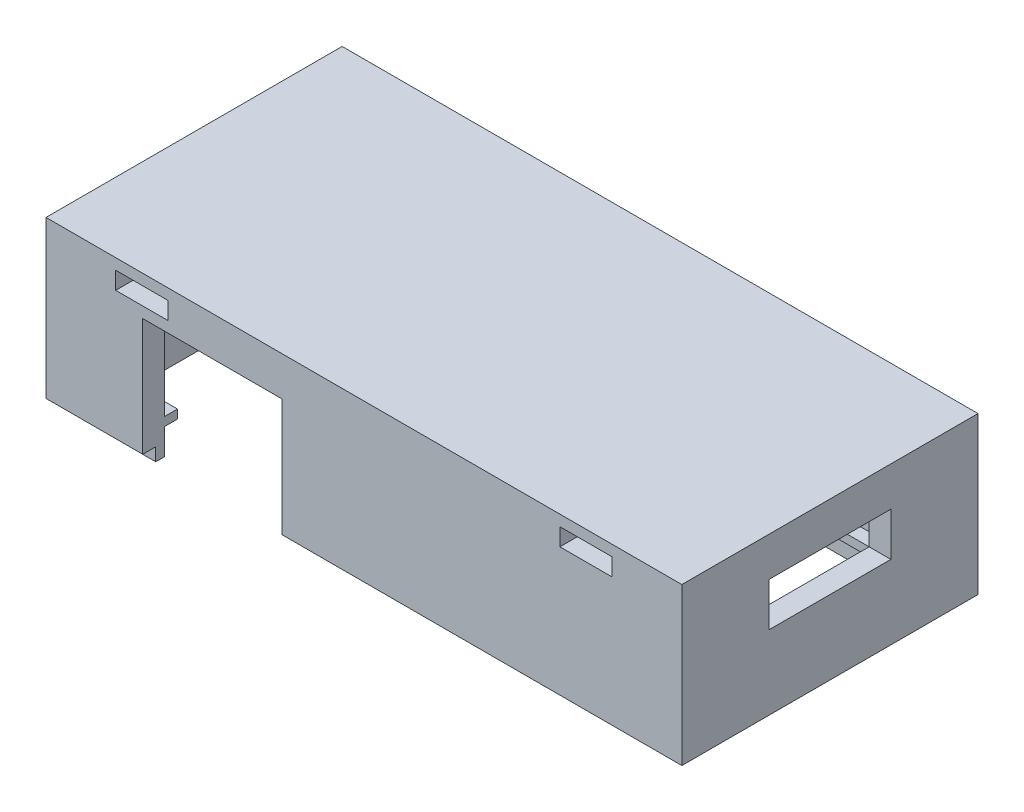
SolidWorks part; units mm, degrees
ref_plane "Front Plane" through (0, 0, 0) normal (0, 0, 1) x (1, 0, 0)
ref_plane "Top Plane" through (0, 0, 0) normal (0, 1, 0) x (1, 0, 0)
ref_plane "Right Plane" through (0, 0, 0) normal (1, 0, 0) x (0, 0, -1)
sketch "Sketch1" plane through (0, 0, 0) normal (0, 1, 0) x (1, 0, 0)
  line L1 (-31.2084, 17.8232) -> (41.7916, 17.8232)
  line L2 (-31.2084, 17.8232) -> (-31.2084, -16.1768)
  line L3 (-31.2084, -16.1768) -> (41.7916, -16.1768)
  line L4 (41.7916, 17.8232) -> (41.7916, -16.1768)
  dimension "D1" = 73
  dimension "D2" = 34
extrude "base" add sketch "Sketch1" along normal blind 4.5
sketch "Sketch21" plane through (0, 0, 0) normal (0, -1, 0) x (-1, 0, 0)
  line L11 (-41.7916, 17.8232) -> (31.2084, 17.8232)
  line L12 (-41.7916, 17.8232) -> (-41.7916, -16.1768)
  line L13 (-41.7916, -16.1768) -> (31.2084, -16.1768)
  line L14 (31.2084, 17.8232) -> (31.2084, -16.1768)
extrude "extrude up" add sketch "Sketch21" along normal blind 13.5
sketch "Sketch22" plane through (0, -13.5, 0) normal (0, -1, 0) x (-1, 0, 0)
  line L0 (-41.7916, 17.8232) -> (-41.7916, -16.1768) construction
  line L1 (-39.2916, 15.3232) -> (28.7084, 15.3232)
  line L2 (-39.2916, 15.3232) -> (-39.2916, -13.6768)
  line L3 (-39.2916, -13.6768) -> (28.7084, -13.6768)
  line L4 (28.7084, 15.3232) -> (28.7084, -13.6768)
  line L5 (31.2084, 17.8232) -> (-41.7916, 17.8232) construction
  line L6 (31.2084, -16.1768) -> (31.2084, 17.8232) construction
  line L7 (-41.7916, -16.1768) -> (31.2084, -16.1768) construction
  dimension "D1" = 2.5
  dimension "D2" = 2.5
  dimension "D3" = 2.5
  dimension "D4" = 2.5
extrude "cut down" cut sketch "Sketch22" against normal blind 13.5
sketch "Sketch27" plane through (0, 0, 0) normal (0, -1, 0) x (1, 0, 0)
  line L0 (-28.7084, -15.3232) -> (39.2916, -15.3232) construction
  line L1 (39.2916, -15.3232) -> (39.2916, 13.6768) construction
  circle A0 centre (31.1416, -11.9232) radius 2
  dimension "D1" = 4
  dimension "D2" = 3.4
  dimension "D3" = 8.15
extrude "Boss-Extrude15" add sketch "Sketch27" along normal blind 1.5 contours A0
sketch "Sketch28" plane through (0, 0, 0) normal (0, -1, 0) x (1, 0, 0)
  line L0 (39.2916, -15.3232) -> (39.2916, 13.6768) construction
  line L1 (39.2916, 13.6768) -> (-28.7084, 13.6768) construction
  circle A0 centre (31.1416, 10.2768) radius 2
  dimension "D1" = 4
  dimension "D2" = 8.15
  dimension "D3" = 3.4
sketch "Sketch29" plane through (0, 0, 0) normal (0, -1, 0) x (1, 0, 0)
  line L0 (-28.7084, -15.3232) -> (39.2916, -15.3232) construction
  circle A0 centre (9.0416, -11.9232) radius 2
  circle A1 centre (31.1416, -11.9232) radius 2 construction
  dimension "D1" = 4
  dimension "D2" = 3.4
  dimension "D3" = 22.1
sketch "Sketch30" plane through (0, 0, 0) normal (0, -1, 0) x (1, 0, 0)
  line L0 (39.2916, 13.6768) -> (-28.7084, 13.6768) construction
  circle A0 centre (9.0416, 10.2768) radius 2
  circle A1 centre (31.1416, 10.2768) radius 2 construction
  dimension "D1" = 4
  dimension "D2" = 3.4
  dimension "D3" = 22.1
extrude "Boss-Extrude16" add sketch "Sketch29" along normal blind 1.5 contours A0
extrude "Boss-Extrude17" add sketch "Sketch30" along normal blind 1.5 contours A0
extrude "Boss-Extrude18" add sketch "Sketch28" along normal blind 1.5 contours A0
sketch "Sketch31" plane through (0, -1.5, 0) normal (0, -1, 0) x (1, 0, 0)
  circle A0 centre (31.1416, -11.9232) radius 1.5
  dimension "D1" = 3
extrude "Boss-Extrude19" add sketch "Sketch31" along normal blind 2
sketch "Sketch32" plane through (0, -1.5, 0) normal (0, -1, 0) x (1, 0, 0)
  circle A0 centre (9.0416, -11.9232) radius 1.5
  circle A1 centre (9.0416, -11.9232) radius 2 construction
  dimension "D1" = 3
  dimension "D2" = 0
extrude "Boss-Extrude20" add sketch "Sketch32" along normal blind 2
sketch "Sketch33" plane through (0, -1.5, 0) normal (0, -1, 0) x (1, 0, 0)
  circle A0 centre (9.0416, 10.2768) radius 1.5
  dimension "D1" = 3
extrude "Boss-Extrude21" add sketch "Sketch33" along normal blind 2
sketch "Sketch34" plane through (0, -1.5, 0) normal (0, -1, 0) x (1, 0, 0)
  circle A0 centre (31.1416, 10.2768) radius 1.5
  dimension "D1" = 3
extrude "Boss-Extrude22" add sketch "Sketch34" along normal blind 2
sketch "Sketch39" plane through (0, 0, -15.3232) normal (0, 0, 1) x (1, 0, 0)
  line L0 (-28.7084, 0) -> (-28.7084, -13.5) construction
  line L1 (-2.2084, -5.5) -> (-21.2084, -5.5)
  line L2 (-2.2084, -5.5) -> (-2.2084, -4.2)
  line L3 (-2.2084, -4.2) -> (-21.2084, -4.2)
  line L4 (-21.2084, -5.5) -> (-21.2084, -4.2)
  line L5 (-28.7084, 0) -> (39.2916, 0) construction
  dimension "D1" = 7.5
  dimension "D2" = 1.3
  dimension "D3" = 4.2
  dimension "D4" = 19
extrude "wall slit" cut sketch "Sketch39" against normal blind 1.5
sketch "Sketch41" plane through (0, 0, 0) normal (0, -1, 0) x (1, 0, 0)
  line L0 (-28.7084, 13.6768) -> (-28.7084, -15.3232) construction
  line L1 (-28.7084, -12.8232) -> (-26.2084, -12.8232)
  line L2 (-28.7084, -12.8232) -> (-28.7084, 11.1768)
  line L3 (-28.7084, 11.1768) -> (-26.2084, 11.1768)
  line L4 (-26.2084, -12.8232) -> (-26.2084, 11.1768)
  line L5 (-28.7084, -15.3232) -> (39.2916, -15.3232) construction
  line L6 (39.2916, 13.6768) -> (-28.7084, 13.6768) construction
  dimension "D1" = 2.5
  dimension "D2" = 2.5
  dimension "D3" = 2.5
extrude "outside block" add sketch "Sketch41" along normal blind 5
sketch "Sketch44" plane through (0, 0, 0) normal (0, -1, 0) x (1, 0, 0)
  line L0 (-28.7084, -15.3232) -> (39.2916, -15.3232) construction
  line L1 (5.2916, -12.8232) -> (2.7916, -12.8232)
  line L2 (5.2916, -12.8232) -> (5.2916, 11.1768)
  line L3 (5.2916, 11.1768) -> (2.7916, 11.1768)
  line L4 (2.7916, -12.8232) -> (2.7916, 11.1768)
  line L5 (39.2916, 13.6768) -> (-28.7084, 13.6768) construction
  line L6 (-26.2084, -12.8232) -> (-26.2084, 11.1768) construction
  dimension "D1" = 2.5
  dimension "D2" = 2.5
  dimension "D3" = 2.5
  dimension "D4" = 29
extrude "inside block" add sketch "Sketch44" along normal blind 5
sketch "Sketch62" plane through (0, -13.5, 0) normal (0, -1, 0) x (1, 0, 0)
  line L0 (41.7916, -17.8232) -> (41.7916, 16.1768) construction
  line L1 (40.2916, -16.3232) -> (-29.7084, -16.3232)
  line L2 (40.2916, -16.3232) -> (40.2916, 14.6768)
  line L3 (40.2916, 14.6768) -> (-29.7084, 14.6768)
  line L4 (-29.7084, -16.3232) -> (-29.7084, 14.6768)
  line L5 (-31.2084, -17.8232) -> (41.7916, -17.8232) construction
  line L6 (41.7916, 16.1768) -> (-4.1084, 16.1768) construction
  line L7 (-31.2084, 16.1768) -> (-31.2084, -17.8232) construction
  dimension "D1" = 1.5
  dimension "D2" = 1.5
  dimension "D3" = 1.5
  dimension "D4" = 1.5
extrude "raise lip" add sketch "Sketch62" along normal blind 1.5
sketch "Sketch74" plane through (0, 0, 13.6768) normal (0, 0, -1) x (-1, 0, 0)
  line L0 (-39.2916, -15) -> (28.7084, -15) construction
  line L1 (20.1084, -15) -> (4.1084, -15)
  line L2 (20.1084, -15) -> (20.1084, 0)
  line L3 (20.1084, 0) -> (4.1084, 0)
  line L4 (4.1084, -15) -> (4.1084, 0)
  line L5 (-39.2916, 0) -> (28.7084, 0) construction
  line L6 (28.7084, 0) -> (28.7084, -13.5) construction
  dimension "D1" = 8.6
  dimension "D2" = 16
extrude "usb hole" cut sketch "Sketch74" against normal blind 2.5
sketch "Sketch63" plane through (0, -15, 0) normal (0, -1, 0) x (1, 0, 0)
  line L0 (40.2916, -16.3232) -> (40.2916, 14.6768) construction
  line L1 (39.2916, -15.3232) -> (-28.7084, -15.3232)
  line L2 (39.2916, -15.3232) -> (39.2916, 13.6768)
  line L3 (39.2916, 13.6768) -> (-28.7084, 13.6768)
  line L4 (-28.7084, -15.3232) -> (-28.7084, 13.6768)
  line L5 (-29.7084, -16.3232) -> (40.2916, -16.3232) construction
  line L6 (40.2916, 14.6768) -> (-4.1084, 14.6768) construction
  line L7 (-29.7084, 14.6768) -> (-29.7084, -16.3232) construction
  dimension "D1" = 1
  dimension "D2" = 1
  dimension "D3" = 1
  dimension "D4" = 1
extrude "cut lip" cut sketch "Sketch63" against normal blind 1.5
sketch "Sketch47" plane through (0, 0, 16.1768) normal (0, 0, 1) x (1, 0, 0)
  line L0 (-31.2084, 4.5) -> (41.7916, 4.5) construction
  line L1 (27.7916, 3.25) -> (33.7916, 3.25)
  line L2 (27.7916, 3.25) -> (27.7916, 1.25)
  line L3 (27.7916, 1.25) -> (33.7916, 1.25)
  line L4 (33.7916, 3.25) -> (33.7916, 1.25)
  line L5 (41.7916, 4.5) -> (41.7916, -13.5) construction
  dimension "D1" = 1.25
  dimension "D2" = 2
  dimension "D3" = 6
  dimension "D4" = 8
extrude "top tie hole" cut sketch "Sketch47" against normal blind 34
sketch "Sketch48" plane through (0, 0, 16.1768) normal (0, 0, 1) x (1, 0, 0)
  line L0 (-31.2084, 4.5) -> (41.7916, 4.5) construction
  line L1 (-23.2084, 3.25) -> (-17.2084, 3.25)
  line L2 (-23.2084, 3.25) -> (-23.2084, 1.25)
  line L3 (-23.2084, 1.25) -> (-17.2084, 1.25)
  line L4 (-17.2084, 3.25) -> (-17.2084, 1.25)
  line L5 (-31.2084, 4.5) -> (-31.2084, -13.5) construction
  dimension "D1" = 6
  dimension "D2" = 2
  dimension "D3" = 1.25
  dimension "D4" = 8
extrude "bottom tie hole" cut sketch "Sketch48" against normal blind 34
sketch "Sketch56" plane through (39.2916, 0, 0) normal (-1, 0, 0) x (0, 0, 1)
  line L0 (-15.3232, 0) -> (-15.3232, -15) construction
  line L1 (6.1768, -5) -> (-7.8232, -5)
  line L2 (6.1768, -5) -> (6.1768, 0)
  line L3 (6.1768, 0) -> (-7.8232, 0)
  line L4 (-7.8232, -5) -> (-7.8232, 0)
  line L5 (-15.3232, 0) -> (13.6768, 0) construction
  dimension "D1" = 14
  dimension "D2" = 7.5
  dimension "D3" = 5
extrude "wire hole" cut sketch "Sketch56" against normal blind 2.5
sketch "Sketch68" plane through (0, 0, -15.3232) normal (0, 0, 1) x (1, 0, 0)
  line L0 (39.2916, 0) -> (39.2916, -15) construction
  line L1 (39.2916, -12) -> (-28.7084, -12)
  line L2 (39.2916, -12) -> (39.2916, -11)
  line L3 (39.2916, -11) -> (-28.7084, -11)
  line L4 (-28.7084, -12) -> (-28.7084, -11)
  line L5 (-28.7084, 0) -> (-28.7084, -15) construction
  line L6 (-28.7084, -15) -> (39.2916, -15) construction
  dimension "D1" = 3
  dimension "D2" = 1
extrude "right ledge" add sketch "Sketch68" along normal blind 1.5
sketch "Sketch67" plane through (0, 0, 13.6768) normal (0, 0, -1) x (-1, 0, 0)
  line L1 (4.1084, -12) -> (-39.2916, -12)
  line L2 (4.1084, -12) -> (4.1084, -11)
  line L3 (4.1084, -11) -> (-39.2916, -11)
  line L4 (-39.2916, -12) -> (-39.2916, -11)
  line L5 (-39.2916, 0) -> (-39.2916, -15) construction
  line L6 (-39.2916, -15) -> (4.1084, -15) construction
  line L9 (28.7084, -12) -> (20.1084, -12)
  line L10 (28.7084, -12) -> (28.7084, -11)
  line L11 (28.7084, -11) -> (20.1084, -11)
  line L12 (20.1084, -12) -> (20.1084, -11)
  line L13 (28.7084, 0) -> (28.7084, -15) construction
  dimension "D1" = 1
  dimension "D2" = 3
  dimension "D3" = 1
  dimension "D4" = 3
extrude "left ledge" add sketch "Sketch67" along normal blind 1.5
sketch "Sketch69" plane through (0, 0, -15.3232) normal (0, 0, 1) x (1, 0, 0)
  line L0 (39.2916, -11) -> (-28.7084, -11) construction
  line L1 (34.2916, -10) -> (23.2916, -10)
  line L2 (34.2916, -10) -> (34.2916, -4)
  line L3 (34.2916, -4) -> (23.2916, -4)
  line L4 (23.2916, -10) -> (23.2916, -4)
  line L5 (39.2916, 0) -> (39.2916, -11) construction
  dimension "D1" = 11
  dimension "D2" = 6
  dimension "D3" = 1
  dimension "D4" = 5
extrude "switch hole" cut sketch "Sketch69" against normal blind 2.5
sketch "Sketch70" plane through (0, 0, -17.8232) normal (0, 0, -1) x (-1, 0, 0)
  line L0 (-23.2916, -4) -> (-23.2916, -10) construction
  line L1 (-6.0464, -10) -> (-13.2916, -10)
  line L2 (-6.0464, -10) -> (-6.0464, -4)
  line L3 (-6.0464, -4) -> (-13.2916, -4)
  line L4 (-13.2916, -10) -> (-13.2916, -4)
  line L5 (-23.2916, -10) -> (-34.2916, -10) construction
  dimension "D1" = 10
  dimension "D2" = 7.2452
  dimension "D3" = 6
  dimension "D4" = 0
extrude "power hole" cut sketch "Sketch70" against normal blind 2.5
